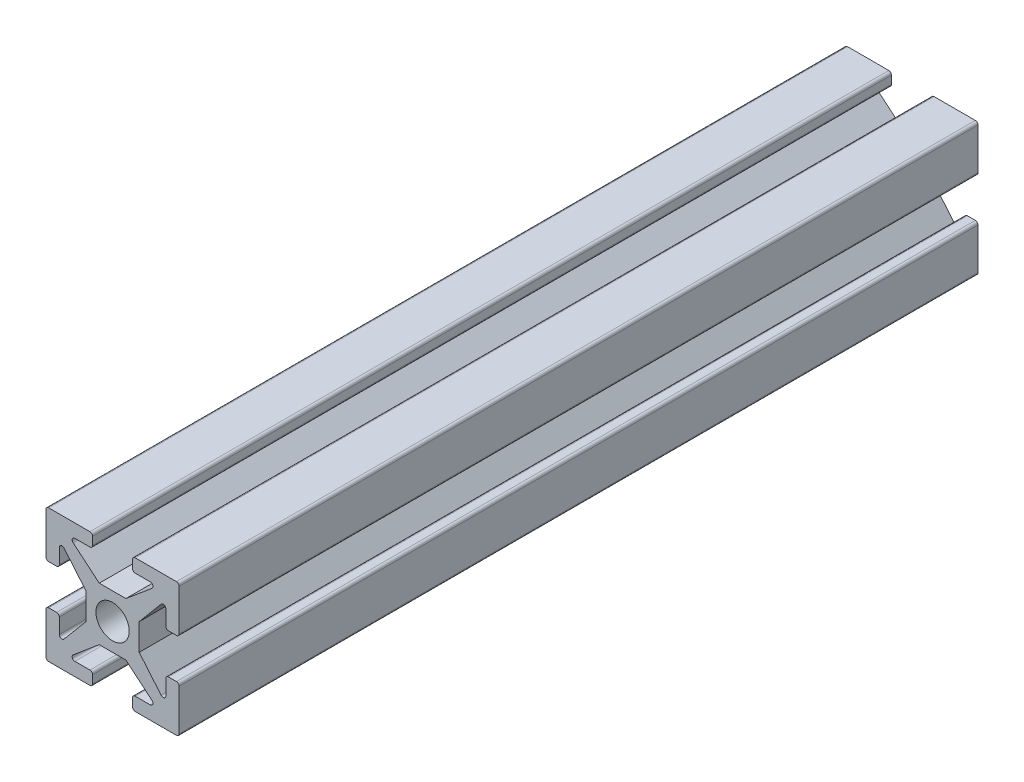
SolidWorks part; units mm, degrees
ref_plane "Front Plane" through (0, 0, 0) normal (0, 0, 1) x (1, 0, 0)
ref_plane "Top Plane" through (0, 0, 0) normal (0, 1, 0) x (1, 0, 0)
ref_plane "Right Plane" through (0, 0, 0) normal (1, 0, 0) x (0, 0, -1)
sketch "Sketch1" plane through (0, 0, 0) normal (0, 0, 1) x (1, 0, 0)
  line L0 (0, 2) -> (0, -2) construction
  line L1 (2.4868, 1) -> (2, 1) construction
  line L2 (2.4868, 1) -> (2.4868, -1) construction
  line L3 (-4.8, 5) -> (-1.7, 5)
  line L4 (2, 2) -> (0, 0) construction
  line L5 (5, 5) -> (0, 0) construction
  line L6 (-5, 5) -> (0, 0) construction
  line L7 (5, 1.7) -> (5, 4.8)
  line L8 (-2, -1) -> (-2, 1)
  line L9 (-1, 2) -> (1, 2)
  line L10 (1, 2) -> (2.9626, 3.6468)
  line L11 (2, 1) -> (3.6468, 2.9626)
  line L12 (-2, 2) -> (0, 0) construction
  line L13 (2.834, 4) -> (1.7, 4)
  line L14 (-5, 0) -> (5, 0) construction
  line L15 (-4, 1.7) -> (-4, 2.834)
  line L16 (-5, 5) -> (-1.5, 5)
  line L17 (-5, 5) -> (-5, 1.5)
  line L18 (-4.8, 1.5) -> (-4.2, 1.5)
  line L19 (-1.5, 4.8) -> (-1.5, 4.2)
  line L20 (-2.834, 4) -> (-1.7, 4)
  line L21 (-2.4868, 1) -> (-2.4868, -1) construction
  line L22 (1.5, 4.8) -> (1.5, 4.2)
  line L23 (-2, 1) -> (-3.6468, 2.9626)
  line L24 (-2.4868, 1) -> (-2, 1) construction
  line L25 (-1, 2) -> (-2.9626, 3.6468)
  line L26 (4.8, 1.5) -> (4.2, 1.5)
  line L27 (-5, 1.7) -> (-5, 4.8)
  line L28 (5, 5) -> (5, 1.5)
  line L29 (5, 5) -> (1.5, 5)
  line L30 (4, 1.7) -> (4, 2.834)
  line L31 (2, -1) -> (2, 1)
  line L32 (4.8, 5) -> (1.7, 5)
  line L33 (-2.4868, -1) -> (-2, -1) construction
  line L34 (-2, -2) -> (0, 0) construction
  line L35 (-5, -5) -> (0, 0) construction
  line L36 (5, -5) -> (0, 0) construction
  line L37 (2, -2) -> (0, 0) construction
  line L38 (2.4868, -1) -> (2, -1) construction
  line L39 (4.8, -5) -> (1.7, -5)
  line L40 (4, -1.7) -> (4, -2.834)
  line L41 (5, -5) -> (1.5, -5)
  line L42 (5, -5) -> (5, -1.5)
  line L43 (-5, -1.7) -> (-5, -4.8)
  line L44 (4.8, -1.5) -> (4.2, -1.5)
  line L45 (-1, -2) -> (-2.9626, -3.6468)
  line L46 (-2, -1) -> (-3.6468, -2.9626)
  line L47 (1.5, -4.8) -> (1.5, -4.2)
  line L48 (-2.834, -4) -> (-1.7, -4)
  line L49 (-1.5, -4.8) -> (-1.5, -4.2)
  line L50 (-4.8, -1.5) -> (-4.2, -1.5)
  line L51 (-5, -5) -> (-5, -1.5)
  line L52 (-5, -5) -> (-1.5, -5)
  line L53 (-4, -1.7) -> (-4, -2.834)
  line L54 (2.834, -4) -> (1.7, -4)
  line L55 (2, -1) -> (3.6468, -2.9626)
  line L56 (1, -2) -> (2.9626, -3.6468)
  line L57 (-1, -2) -> (1, -2)
  line L58 (5, -1.7) -> (5, -4.8)
  line L59 (-4.8, -5) -> (-1.7, -5)
  circle A0 centre (0, 0) radius 1.25
  arc A1 (-2.9626, 3.6468) -> (-2.834, 4) centre (-2.834, 3.8) cw
  arc A2 (-3.6468, 2.9626) -> (-4, 2.834) centre (-3.8, 2.834) ccw
  arc A3 (-1.7, 4) -> (-1.5, 4.2) centre (-1.7, 4.2) ccw
  arc A4 (-4, 1.7) -> (-4.2, 1.5) centre (-4.2, 1.7) cw
  arc A5 (-1.7, 5) -> (-1.5, 4.8) centre (-1.7, 4.8) cw
  arc A6 (-5, 1.7) -> (-4.8, 1.5) centre (-4.8, 1.7) ccw
  arc A7 (-5, 4.8) -> (-4.8, 5) centre (-4.8, 4.8) cw
  arc A8 (5, 4.8) -> (4.8, 5) centre (4.8, 4.8) ccw
  arc A9 (5, 1.7) -> (4.8, 1.5) centre (4.8, 1.7) cw
  arc A10 (1.7, 5) -> (1.5, 4.8) centre (1.7, 4.8) ccw
  arc A11 (4, 1.7) -> (4.2, 1.5) centre (4.2, 1.7) ccw
  arc A12 (1.7, 4) -> (1.5, 4.2) centre (1.7, 4.2) cw
  arc A13 (3.6468, 2.9626) -> (4, 2.834) centre (3.8, 2.834) cw
  arc A14 (2.9626, 3.6468) -> (2.834, 4) centre (2.834, 3.8) ccw
  arc A15 (2.9626, -3.6468) -> (2.834, -4) centre (2.834, -3.8) cw
  arc A16 (3.6468, -2.9626) -> (4, -2.834) centre (3.8, -2.834) ccw
  arc A17 (1.7, -4) -> (1.5, -4.2) centre (1.7, -4.2) ccw
  arc A18 (4, -1.7) -> (4.2, -1.5) centre (4.2, -1.7) cw
  arc A19 (1.7, -5) -> (1.5, -4.8) centre (1.7, -4.8) cw
  arc A20 (5, -1.7) -> (4.8, -1.5) centre (4.8, -1.7) ccw
  arc A21 (5, -4.8) -> (4.8, -5) centre (4.8, -4.8) cw
  arc A22 (-5, -4.8) -> (-4.8, -5) centre (-4.8, -4.8) ccw
  arc A23 (-5, -1.7) -> (-4.8, -1.5) centre (-4.8, -1.7) cw
  arc A24 (-1.7, -5) -> (-1.5, -4.8) centre (-1.7, -4.8) ccw
  arc A25 (-4, -1.7) -> (-4.2, -1.5) centre (-4.2, -1.7) ccw
  arc A26 (-1.7, -4) -> (-1.5, -4.2) centre (-1.7, -4.2) cw
  arc A27 (-3.6468, -2.9626) -> (-4, -2.834) centre (-3.8, -2.834) cw
  arc A28 (-2.9626, -3.6468) -> (-2.834, -4) centre (-2.834, -3.8) ccw
  point P0 (0, 0)
  point P4 (-3.3835, 4)
  point P6 (0, 0)
  point P7 (2, 0)
  point P10 (3.3835, -4)
  point P14 (-4, 3.3835)
  point P71 (4, 3.3835)
  point P72 (3.3835, 4)
  point P75 (-2.4868, 0)
  point P80 (2.4868, 0)
  point P129 (-2, 0)
  point P130 (4, -3.3835)
  point P131 (-4, -3.3835)
  point P132 (-3.3835, -4)
  dimension "D5" = 2.5
  dimension "D2" = 0.2
  dimension "D6" = 1.5
  dimension "D8" = 1
  dimension "D10" = 50
extrude "Boss-Extrude1" add sketch "Sketch1" along normal blind 60 contours A28 L45 L57 L56 A15 L54 A17 L47 A19 L39 A21 L42 A20 L44 A18 L40 A16 L55 L31 L11 A13 L30 A11 L26 A9 L7 A8 L29 A10 L22 A12 L13 A14 L10 L9 L25 A1 L20 A3 L19 A5 L3 A7 L17 A6 L18 A4 L15 A2 L23 L8
ref_point "Point1"
ref_point "Point2"
ref_plane "SYM" through (0, 0, 30) normal (0, 0, 1) x (1, 0, 0)
